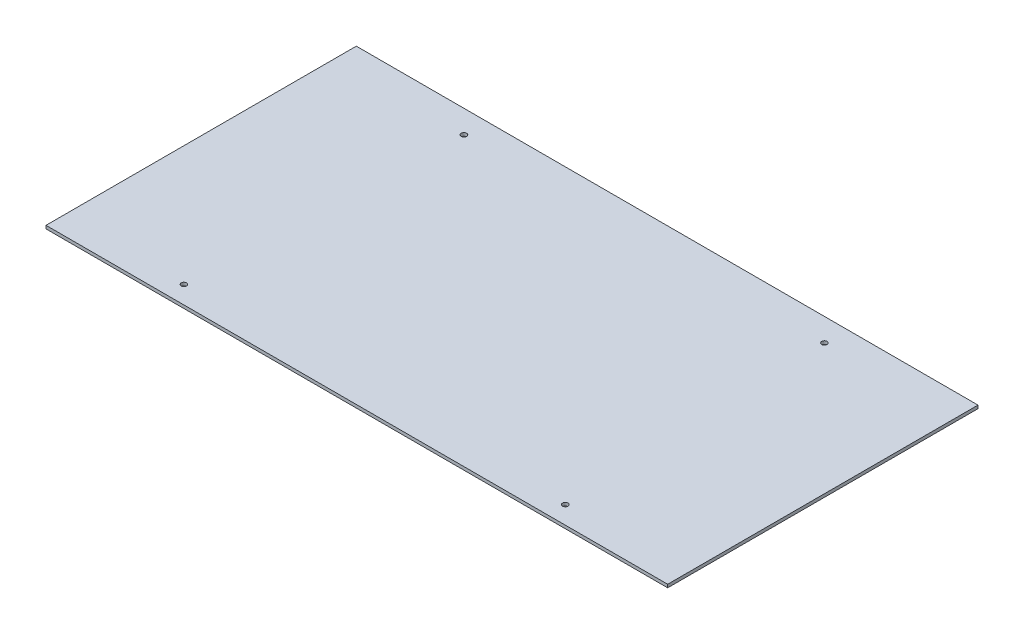
SolidWorks part; units mm, degrees
ref_plane "Front Plane" through (0, 0, 0) normal (0, 0, 1) x (1, 0, 0)
ref_plane "Top Plane" through (0, 0, 0) normal (0, 1, 0) x (1, 0, 0)
ref_plane "Right Plane" through (0, 0, 0) normal (1, 0, 0) x (0, 0, -1)
sketch "Sketch1" plane through (0, 0, 0) normal (0, 1, 0) x (1, 0, 0)
  line L1 (-297.5, 148.5) -> (297.5, 148.5)
  line L2 (-297.5, 148.5) -> (-297.5, -148.5)
  line L3 (-297.5, -148.5) -> (297.5, -148.5)
  line L4 (297.5, 148.5) -> (297.5, -148.5)
  line L5 (-297.5, 148.5) -> (297.5, -148.5) construction
  line L6 (-297.5, -148.5) -> (297.5, 148.5) construction
  point P0 (0, 0)
  dimension "D1" = 595
  dimension "D2" = 297
extrude "Boss-Extrude1" add sketch "Sketch1" along normal blind 3
sketch "Sketch2" plane through (0, 0, 0) normal (0, -1, 0) x (1, 0, 0)
  line L0 (297.5, 148.5) -> (297.5, -148.5) construction
  line L1 (-297.5, 148.5) -> (297.5, 148.5) construction
  circle A0 centre (182.5, 131.5) radius 2.6
  circle A1 centre (-182.5, 131.5) radius 2.6
  dimension "D1" = 17
  dimension "D3" = 480
  dimension "D4" = 5.2
  dimension "D5" = 5.2
  dimension "D2" = 115
  dimension "D6" = 17
extrude "Cut-Extrude1" cut sketch "Sketch2" against normal through all both and the other way through all
sketch "Sketch3" plane through (0, 0, 0) normal (0, -1, 0) x (-1, 0, 0)
  circle A0 centre (-172.5, 126.5) radius 2.6
  circle A1 centre (172.5, 126.5) radius 2.6
extrude "Cut-Extrude2" cut sketch "Sketch3" against normal through all both
